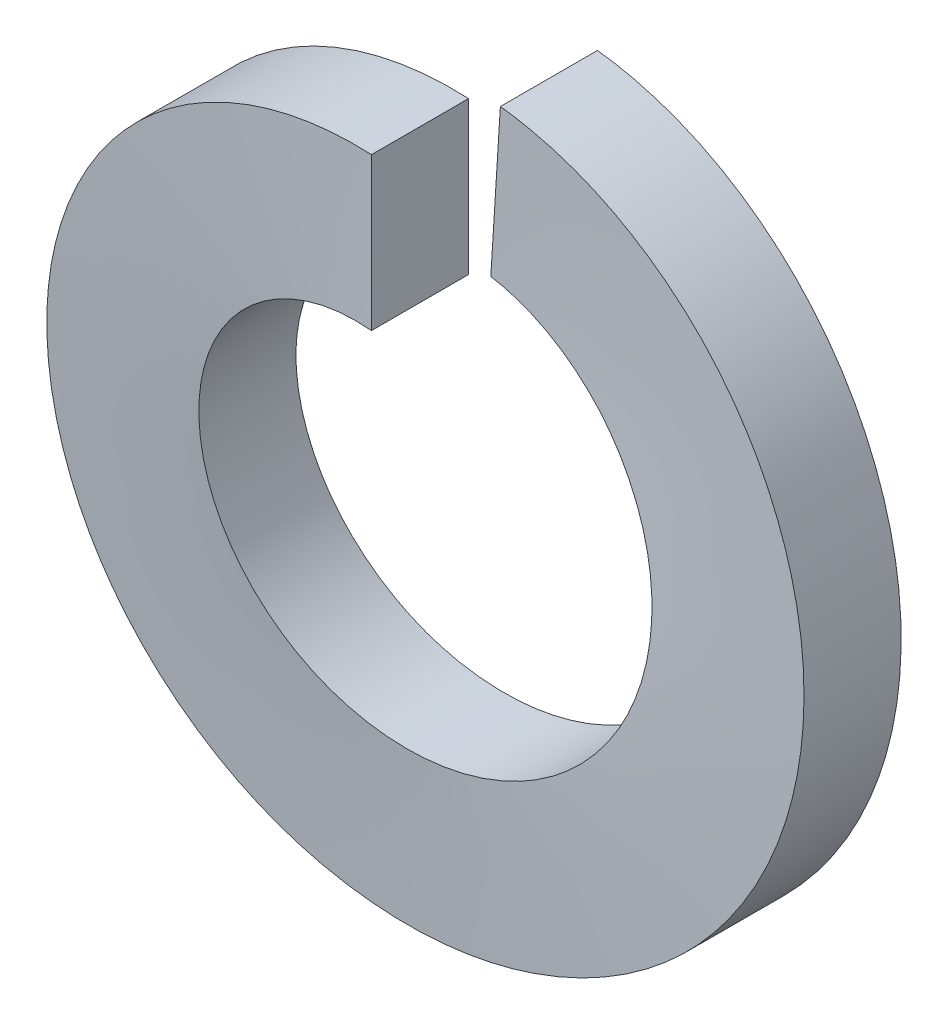
SolidWorks part; units mm, degrees
ref_plane "Front Plane" through (0, 0, 0) normal (0, 0, 1) x (1, 0, 0)
ref_plane "Top Plane" through (0, 0, 0) normal (0, 1, 0) x (1, 0, 0)
ref_plane "Right Plane" through (0, 0, 0) normal (1, 0, 0) x (0, 0, -1)
sketch "Sketch1" plane through (0, 0, 0) normal (0, 0, 1) x (1, 0, 0)
  line L0 (0, 8.636) -> (0, 4.8895) construction
  circle A0 centre (0, 0) radius 8.636
  circle A1 centre (0, 0) radius 4.8895 construction
  dimension "ID" = 9.779
  dimension "OD" = 17.272
curve "Helix/Spiral1" pitch 2.6529 height 2.6264 turns 0.99 parameters "HT"=2.6264
sketch "Sketch2" plane through (0, 0, 0) normal (1, 0, 0) x (0, 0, -1)
  line L1 (0, 8.636) -> (-2.3876, 8.636)
  line L2 (0, 8.636) -> (0, 4.8895)
  line L3 (0, 4.8895) -> (-2.3876, 4.8895)
  line L4 (-2.3876, 8.636) -> (-2.3876, 4.8895)
  dimension "THK" = 2.3876
sweep "Sweep1" add profiles "Sketch2" path "Helix/Spiral1"
equation "\"HT@Helix/Spiral1\" = \"THK@Sketch2\"*1.1"
